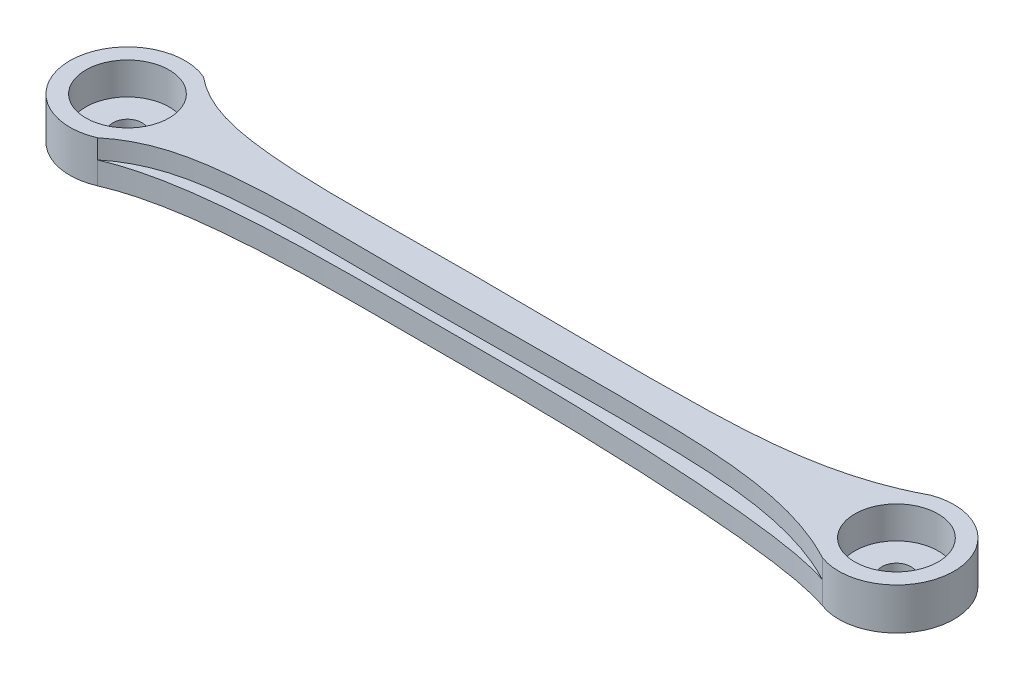
SolidWorks part; units mm, degrees
ref_plane "Front" through (0, 0, 0) normal (0, 0, 1) x (1, 0, 0)
ref_plane "Top" through (0, 0, 0) normal (0, 1, 0) x (1, 0, 0)
ref_plane "Right" through (0, 0, 0) normal (1, 0, 0) x (0, 0, -1)
sketch "Sketch1" plane through (0, 0, 0) normal (0, 1, 0) x (1, 0, 0)
  line L0 (-160.4656, 0) -> (44.4663, 0) construction
  line L1 (-106.6934, 4.0258) -> (-126.1258, 12.4799) construction
  line L2 (4.9211, 11.3545) -> (-11.0509, 5.5696) construction
  line L3 (-48.5627, 4) -> (-76.4251, 4) construction
  circle A0 centre (-120, 0) radius 2.25
  circle A1 centre (0, 0) radius 2.25
  circle A2 centre (-120, 0) radius 9
  circle A3 centre (0, 0) radius 9
  spline S0 degree 3 poles (-116.4096, 8.2528) (-105.4789, 3.4974) (-80.5324, 4.1285) (-45.7009, 3.8926) (-12.0492, 5.208) (-3.0649, 8.4621) knots 0 0 0 0 0.514413 0.614413 1 1 1 1
  spline S1 degree 3 poles (-116.4096, -8.2528) (-105.4789, -3.4974) (-80.5324, -4.1285) (-45.7009, -3.8926) (-12.0492, -5.208) (-3.0649, -8.4621) knots 0 0 0 0 0.514413 0.614413 1 1 1 1
  point P11 (-62.3277, 2.5521)
  point P13 (-113.9747, 6.6855)
  point P14 (0, 0)
  point P15 (0, 0)
  point P18 (0, 0)
  point P20 (-120, 9)
  point P22 (-62.1973, 2.9344)
  point P23 (0, 0)
  point P24 (0, 0)
  dimension "D1" = 4.5
  dimension "D2" = 4.5
  dimension "D4" = 18
  dimension "D5" = 18
  dimension "D6" = 60
  dimension "D3" = 120
  dimension "D7" = 4
extrude "Boss-Extrude1" add sketch "Sketch1" along normal blind 6.5 contours A2 A0 | A2 S1 A3 S0 | A3 A1
sketch "Sketch2" plane through (0, 6.5, 0) normal (0, 1, 0) x (1, 0, 0)
  circle A0 centre (-120, 0) radius 6.5
  circle A1 centre (0, 0) radius 6.5
  dimension "D1" = 13
  dimension "D2" = 13
extrude "Cut-Extrude1" cut sketch "Sketch2" against normal blind 5
sketch "Sketch3" plane through (0, 6.5, 0) normal (0, 1, 0) x (1, 0, 0)
  line L0 (-137.6146, 0) -> (18.7805, 0) construction
  circle A0 centre (-120, 0) radius 6.5 construction
  circle A1 centre (0, 0) radius 6.5 construction
  circle A4 centre (-120, 0) radius 6.5
  circle A5 centre (0, 0) radius 6.5
  spline S0 degree 3 poles (1619.3029, 998.9257) (-352.9389, -13.1279) (-163.7052, 4.6916) (3.3612, 3.5604) (324.0175, 24.8705) (-1993.8382, 196.3398) knots -2.387867 -2.387867 -2.387867 -2.387867 0.514413 0.614413 2.408556 2.408556 2.408556 2.408556 only from (-116.4096, 8.2528) to (-3.0649, 8.4621) construction
  spline S1 degree 3 poles (1619.3029, -998.9257) (-352.9389, 13.1279) (-163.7052, -4.6916) (3.3612, -3.5604) (324.0175, -24.8705) (-1993.8382, -196.3398) knots -2.387867 -2.387867 -2.387867 -2.387867 0.514413 0.614413 2.408556 2.408556 2.408556 2.408556 only from (-116.4096, -8.2528) to (-3.0649, -8.4621) construction
  spline S2 degree 3 poles (-116.4096, 8.2528) (-105.4789, 3.4974) (-80.5324, 4.1285) (-45.7009, 3.8926) (-12.0492, 5.208) (-3.0649, 8.4621) knots 0 0 0 0 0.514413 0.614413 1 1 1 1
  spline S3 degree 3 poles (-116.4096, -8.2528) (-105.4789, -3.4974) (-80.5324, -4.1285) (-45.7009, -3.8926) (-12.0492, -5.208) (-3.0649, -8.4621) knots 0 0 0 0 0.514413 0.614413 1 1 1 1
  spline S4 degree 3 poles (-116.4096, -8.2528) (-111.9265, -4.5151) (-103.6152, -3.0078) (-91.2207, -2.3473) (-77.849, -2.5685) (-58.0096, -2.5341) (-32.0985, -2.1177) (-12.4421, -3.4521) (-3.0649, -8.4621) knots 0 0 0 0 0.145433 0.214932 0.323765 0.493222 0.731337 1 1 1 1
  spline S5 degree 3 poles (-116.4096, 8.2528) (-111.9265, 4.5151) (-103.6152, 3.0078) (-91.2207, 2.3473) (-77.849, 2.5685) (-58.0096, 2.5341) (-32.0985, 2.1177) (-12.4421, 3.4521) (-3.0649, 8.4621) knots 0 0 0 0 0.145433 0.214932 0.323765 0.493222 0.731337 1 1 1 1
  point P16 (-60.6545, -2.4898)
  spline M5 degree 3 poles (-116.4096, -8.2528) (-105.4789, -3.4974) (-80.5324, -4.1285) (-45.7009, -3.8926) (-12.0492, -5.208) (-3.0649, -8.4621) knots 0 0 0 0 0.514413 0.614413 1 1 1 1
  spline M7 degree 3 poles (-3.0649, 8.4621) (-12.0492, 5.208) (-45.7009, 3.8926) (-80.5324, 4.1285) (-105.4789, 3.4974) (-116.4096, 8.2528) knots 0 0 0 0 0.385587 0.485587 1 1 1 1
  dimension "D1" = 2.5
  dimension "D2" = 2.5
  dimension "D3" = 2.5
  dimension "D4" = 2.5
extrude "Cut-Extrude2" cut sketch "Sketch3" against normal blind 3 contours S4 M5 | S5 M7
